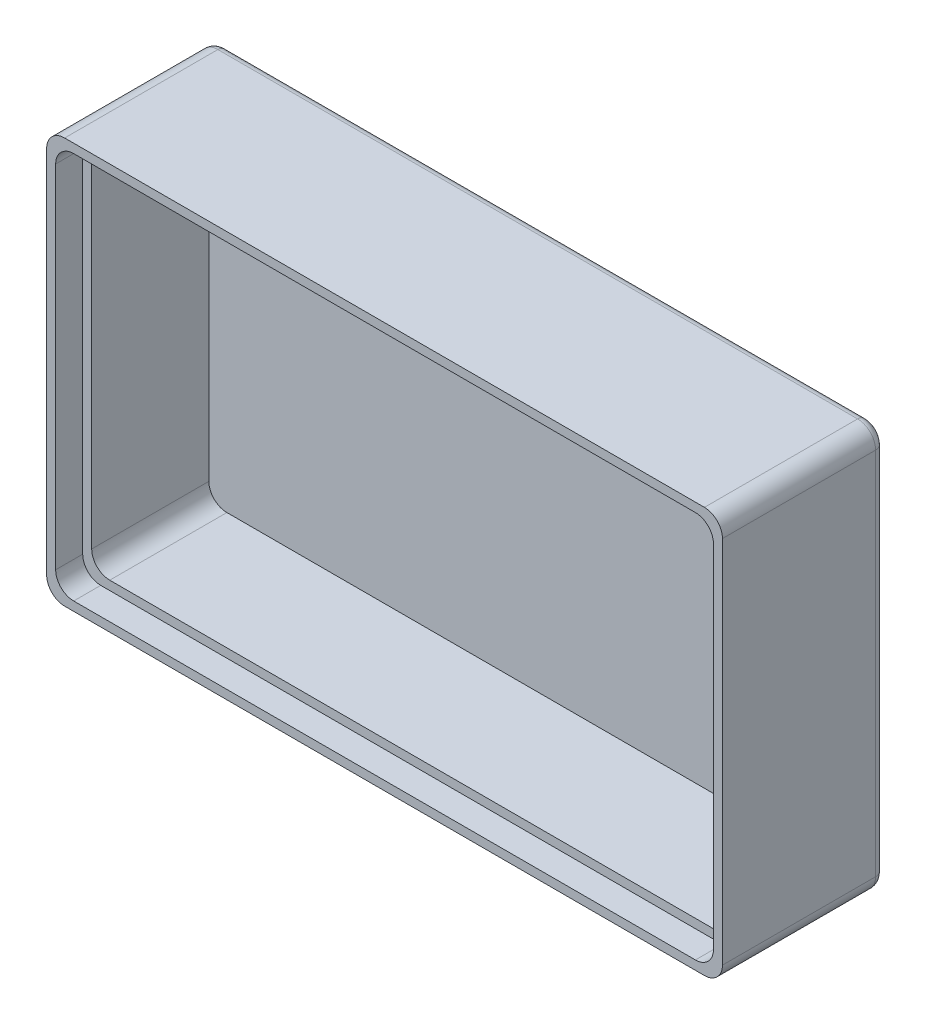
SolidWorks part; units mm, degrees
material "ABS"
ref_plane "前视基准面" through (0, 0, 0) normal (0, 0, 1) x (1, 0, 0)
ref_plane "上视基准面" through (0, 0, 0) normal (0, 1, 0) x (1, 0, 0)
ref_plane "右视基准面" through (0, 0, 0) normal (1, 0, 0) x (0, 0, -1)
sketch "草图1" plane through (0, 0, 0) normal (0, 0, 1) x (1, 0, 0)
  line L1 (-37.5, 22.5) -> (37.5, 22.5)
  line L2 (-37.5, 22.5) -> (-37.5, -22.5)
  line L3 (-37.5, -22.5) -> (37.5, -22.5)
  line L4 (37.5, 22.5) -> (37.5, -22.5)
  dimension "D1" = 75
  dimension "D2" = 45
  dimension "D3" = 37.5
  dimension "D4" = 22.5
extrude "凸台-拉伸1" add sketch "草图1" along normal blind 18
sketch "草图2" plane through (0, 0, 18) normal (0, 0, 1) x (1, 0, 0)
  line L0 (-35.5, 20.5) -> (-35.5, -20.5)
  line L1 (-35.5, -20.5) -> (35.5, -20.5)
  line L2 (35.5, -20.5) -> (35.5, 20.5)
  line L3 (35.5, 20.5) -> (-35.5, 20.5)
extrude "切除-拉伸1" cut sketch "草图2" against normal blind 16
sketch "草图3" plane through (0, 0, 18) normal (0, 0, 1) x (1, 0, 0)
  line L0 (-35.5, -20.5) -> (35.5, -20.5) construction
  line L1 (35.5, -20.5) -> (35.5, 20.5) construction
  line L2 (35.5, 20.5) -> (-35.5, 20.5) construction
  line L3 (-35.5, 20.5) -> (-35.5, -20.5) construction
  line L4 (-35.5, -20.5) -> (35.5, -20.5)
  line L5 (35.5, -20.5) -> (35.5, 20.5)
  line L6 (35.5, 20.5) -> (-35.5, 20.5)
  line L7 (-35.5, 20.5) -> (-35.5, -20.5)
  line L8 (-36.5, -21.5) -> (36.5, -21.5)
  line L9 (36.5, -21.5) -> (36.5, 21.5)
  line L10 (36.5, 21.5) -> (-36.5, 21.5)
  line L11 (-36.5, 21.5) -> (-36.5, -21.5)
  dimension "D1" = 1
extrude "切除-拉伸2" cut sketch "草图3" against normal blind 3
fillet "圆角1" radius 2 12 edges at (-37.5, -22.5, 9) (37.5, -22.5, 9) (37.5, 22.5, 9) (-37.5, 22.5, 9) (-35.5, 20.5, 8.5) (35.5, 20.5, 8.5) (35.5, -20.5, 8.5) (-35.5, -20.5, 8.5) (-36.5, -21.5, 16.5) (36.5, -21.5, 16.5) (36.5, 21.5, 16.5) (-36.5, 21.5, 16.5)
fillet "圆角2" radius 1 8 edges at (36.9142, -21.9142, 0) (37.5, 0, 0) (36.9142, 21.9142, 0) (0, 22.5, 0) (-36.9142, 21.9142, 0) (-37.5, 0, 0) (-36.9142, -21.9142, 0) (0, -22.5, 0)
sketch3d "URDF Reference"
  line L0 (0, 0, 0) -> (10, 0, 0) construction
  line L1 (0, 0, 0) -> (0, 10, 0) construction
  point P0 (0, 0, 0)
  point P1 (0, 0, 0)
